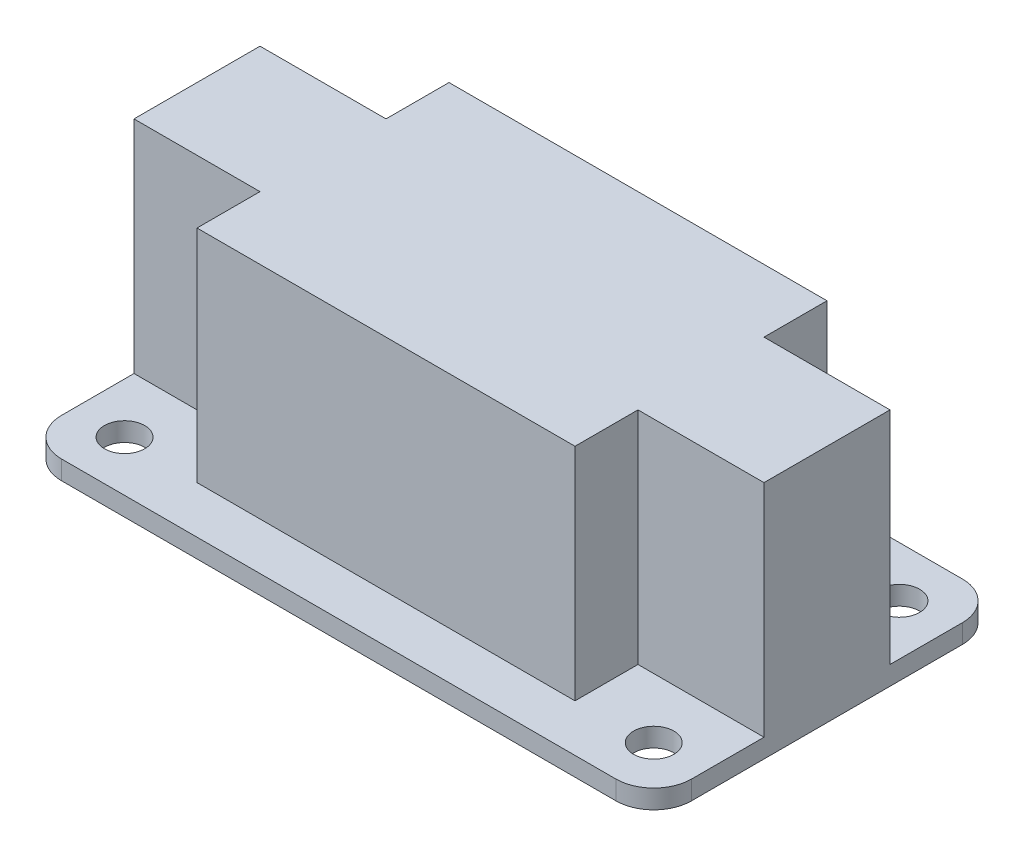
SolidWorks part; units mm, degrees
ref_plane "Front Plane" through (0, 0, 0) normal (0, 0, 1) x (1, 0, 0)
ref_plane "Top Plane" through (0, 0, 0) normal (0, 1, 0) x (1, 0, 0)
ref_plane "Right Plane" through (0, 0, 0) normal (1, 0, 0) x (0, 0, -1)
sketch "Sketch2" plane through (0, 0, 0) normal (0, 1, 0) x (1, 0, 0)
  line L0 (25, 27.5) -> (25, 0) construction
  line L1 (0, 0) -> (50, 0)
  line L2 (0, 0) -> (0, 27.5)
  line L3 (0, 27.5) -> (50, 27.5)
  line L4 (50, 0) -> (50, 27.5)
  line L5 (0, 13.75) -> (50, 13.75) construction
  line L7 (4, 4) -> (46, 4)
  line L8 (4, 4) -> (4, 23.5)
  line L9 (4, 23.5) -> (46, 23.5)
  line L10 (46, 4) -> (46, 23.5)
  line L11 (4, 4) -> (46, 23.5) construction
  line L12 (4, 23.5) -> (46, 4) construction
  circle A0 centre (46, 23.5) radius 1.6
  circle A1 centre (46, 4) radius 1.6
  circle A2 centre (4, 23.5) radius 1.6
  circle A3 centre (4, 4) radius 1.6
  point P9 (25, 13.75)
  dimension "D5" = 3.2
  dimension "D6" = 3.2
  dimension "D7" = 3.2
  dimension "D8" = 3.2
  dimension "D1" = 50
  dimension "D2" = 27.5
  dimension "D3" = 4
  dimension "D4" = 4
extrude "Boss-Extrude1" add sketch "Sketch2" along normal blind 1.5 contours L1 L4 L3 L2 A3 L8 A2 L9 A0 L10 A1 L7 | A3 L7 A1 L10 A0 L9 A2 L8
fillet "Fillet1" radius 3 4 edges at (0, 0.75, -27.5) (0, 0.75, 0) (50, 0.75, -27.5) (50, 0.75, 0)
sketch "Sketch3" plane through (0, 0, 0) normal (0, 1, 0) x (1, 0, 0)
  line L0 (0, 13.75) -> (50, 13.75) construction
  line L5 (0, 3) -> (0, 24.5) construction
  line L6 (50, 3) -> (50, 24.5) construction
  line L8 (10, 8.75) -> (0, 8.75)
  line L9 (10, 8.75) -> (10, 18.75)
  line L10 (10, 18.75) -> (0, 18.75)
  line L11 (0, 8.75) -> (0, 18.75)
  line L12 (10, 8.75) -> (0, 18.75) construction
  line L13 (10, 18.75) -> (0, 8.75) construction
  line L14 (40, 3.75) -> (10, 3.75)
  line L15 (40, 3.75) -> (40, 23.75)
  line L16 (40, 23.75) -> (10, 23.75)
  line L17 (10, 3.75) -> (10, 23.75)
  line L18 (40, 3.75) -> (10, 23.75) construction
  line L19 (40, 23.75) -> (10, 3.75) construction
  line L20 (40, 8.75) -> (50, 8.75)
  line L21 (40, 8.75) -> (40, 18.75)
  line L22 (40, 18.75) -> (50, 18.75)
  line L23 (50, 8.75) -> (50, 18.75)
  line L24 (40, 8.75) -> (50, 18.75) construction
  line L25 (40, 18.75) -> (50, 8.75) construction
  point P0 (5, 13.75)
  point P11 (25, 13.75)
  point P16 (45, 13.75)
  dimension "D1" = 10
  dimension "D2" = 10
  dimension "D3" = 30
  dimension "D4" = 20
  dimension "D5" = 10
extrude "Boss-Extrude2" add sketch "Sketch3" along normal blind 19 contours L11 L8 L9 L10 | L17 L14 L15 L16 L9 | L20 L23 L22 L15
